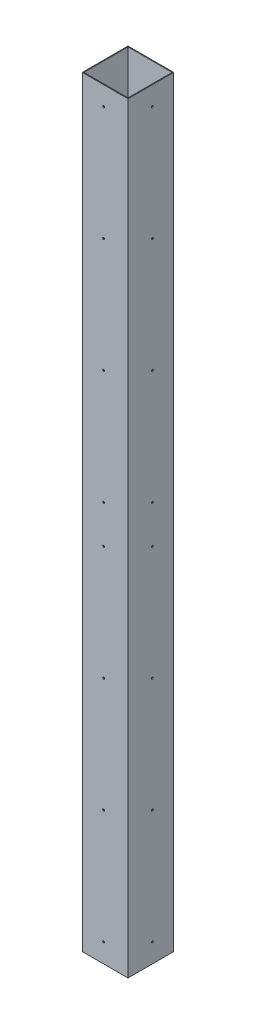
SolidWorks part; units mm, degrees
material "1350 合金"
ref_plane "前视基准面" through (0, 0, 0) normal (0, 0, 1) x (1, 0, 0)
ref_plane "上视基准面" through (0, 0, 0) normal (0, 1, 0) x (1, 0, 0)
ref_plane "右视基准面" through (0, 0, 0) normal (1, 0, 0) x (0, 0, -1)
sketch "草图1" plane through (0, 0, 0) normal (0, 1, 0) x (1, 0, 0)
  line L1 (-60, 60) -> (60, 60)
  line L2 (-60, 60) -> (-60, -60)
  line L3 (-60, -60) -> (60, -60)
  line L4 (60, 60) -> (60, -60)
  point P4 (0, 60)
  point P6 (60, 0)
  dimension "D1" = 120
extrude "拉伸-薄壁1" add sketch "草图1" along normal blind 2000 thin
sketch "草图2" plane through (0, 0, 0) normal (1, 0, 0) x (0, 0, -1)
  line L0 (-60, 0) -> (60, 0) construction
  line L1 (60, 2000) -> (60, 0) construction
  circle A0 centre (4, 50) radius 2.5
  circle A1 centre (4, 350) radius 2.5
  circle A2 centre (4, 650) radius 2.5
  circle A3 centre (4, 950) radius 2.5
  circle A4 centre (4, 1950) radius 2.5
  circle A5 centre (4, 1650) radius 2.5
  circle A6 centre (4, 1350) radius 2.5
  circle A7 centre (4, 1050) radius 2.5
  dimension "D1" = 5
  dimension "D2" = 50
  dimension "D3" = 56
  dimension "D5" = 300
  dimension "D4" = 4
  dimension "D6" = 2
extrude "切除-拉伸1" cut sketch "草图2" along normal through all
sketch "草图3" plane through (0, 0, 0) normal (0, 0, 1) x (1, 0, 0)
  line L2 (-60, 2000) -> (-60, 0) construction
  line L3 (-60, 0) -> (60, 0) construction
  circle A0 centre (-4, 50) radius 2.5
  circle A1 centre (-4, 350) radius 2.5
  circle A2 centre (-4, 650) radius 2.5
  circle A3 centre (-4, 950) radius 2.5
  circle A4 centre (-4, 1950) radius 2.5
  circle A5 centre (-4, 1650) radius 2.5
  circle A6 centre (-4, 1350) radius 2.5
  circle A7 centre (-4, 1050) radius 2.5
  dimension "D1" = 5
  dimension "D2" = 56
  dimension "D3" = 50
  dimension "D5" = 300
  dimension "D4" = 4
  dimension "D6" = 2
extrude "切除-拉伸2" cut sketch "草图3" along normal through all
